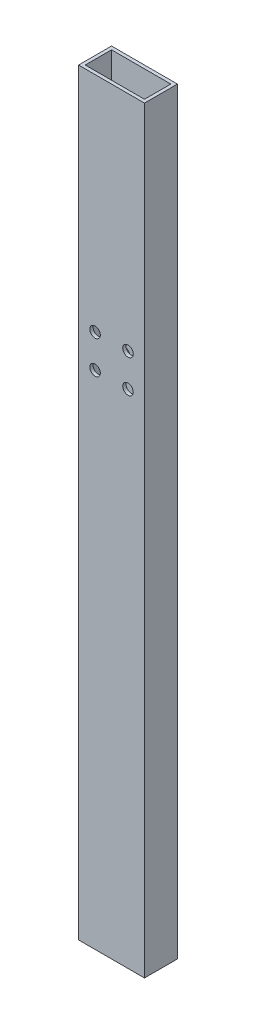
SolidWorks part; units mm, degrees
ref_plane "前视基准面" through (0, 0, 0) normal (0, 0, 1) x (1, 0, 0)
ref_plane "上视基准面" through (0, 0, 0) normal (0, 1, 0) x (1, 0, 0)
ref_plane "右视基准面" through (0, 0, 0) normal (1, 0, 0) x (0, 0, -1)
other "Configuration Table"
sketch "草图1" plane through (0, 0, 0) normal (0, 1, 0) x (1, 0, 0)
  line L1 (-10, -5) -> (10, -5)
  line L2 (-10, -5) -> (-10, 5)
  line L3 (-10, 5) -> (10, 5)
  line L4 (10, -5) -> (10, 5)
  line L5 (-10, -5) -> (10, 5) construction
  line L6 (-10, 5) -> (10, -5) construction
  point P0 (0, 0)
  dimension "D1" = 20
  dimension "D2" = 10
extrude "拉伸-薄壁1" add sketch "草图1" along normal blind 230 thin thin type one direction reverse wall 1
sketch "草图3" plane through (0, 0, 5) normal (0, 0, 1) x (1, 0, 0)
  line L0 (-10, 157.3) -> (10, 157.3) construction
  line L1 (-10, 230) -> (10, 230) construction
  line L3 (0, 157.3) -> (0, 230) construction
  line L4 (-10, 115) -> (10, 115) construction
  line L5 (-10, 230) -> (-10, 0) construction
  line L6 (10, 230) -> (10, 0) construction
  circle A0 centre (-5, 162.3) radius 1.6
  circle A1 centre (-5, 152.3) radius 1.6
  circle A2 centre (5, 152.3) radius 1.6
  circle A3 centre (5, 162.3) radius 1.6
  dimension "D1" = 3.2
  dimension "D2" = 10
  dimension "D3" = 10
  dimension "D4" = 42.3
extrude "切除-拉伸1" cut sketch "草图3" against normal through all
